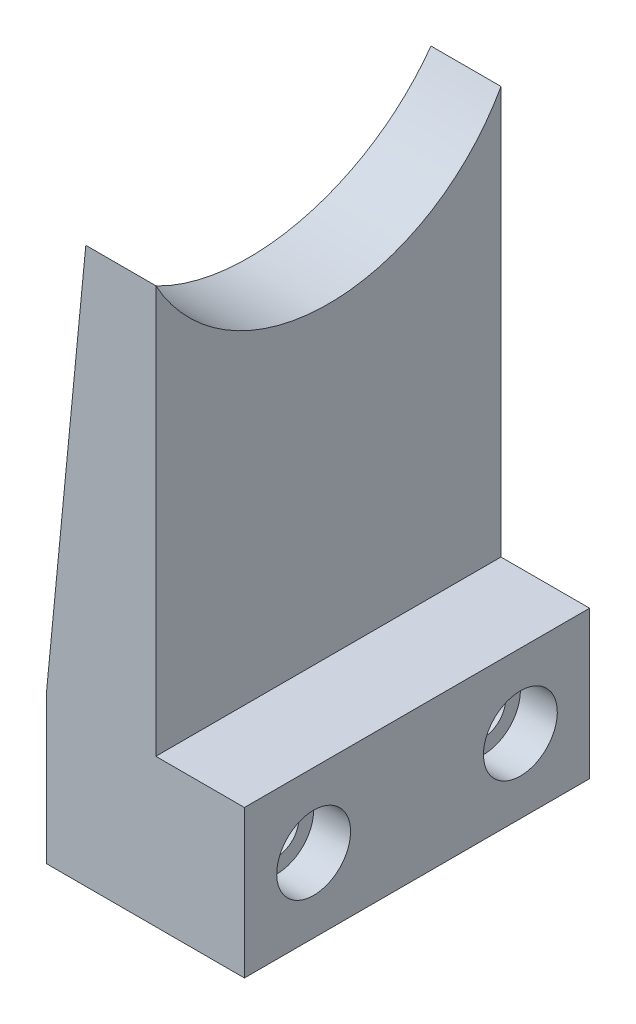
SolidWorks part; units mm, degrees
ref_plane "Front Plane" through (0, 0, 0) normal (0, 0, 1) x (1, 0, 0)
ref_plane "Top Plane" through (0, 0, 0) normal (0, 1, 0) x (1, 0, 0)
ref_plane "Right Plane" through (0, 0, 0) normal (1, 0, 0) x (0, 0, -1)
sketch "Gripper Attachment Base Sketch" plane through (0, 0, 0) normal (0, 0, 1) x (1, 0, 0)
  line L5 (5.5563, 7.5) -> (-5.5562, 7.5)
  line L6 (5.5563, 7.5) -> (5.5563, -7.5)
  line L7 (5.5563, -7.5) -> (-5.5562, -7.5)
  line L8 (-5.5562, 7.5) -> (-5.5562, -7.5)
  line L9 (5.5563, 7.5) -> (-5.5562, -7.5) construction
  line L10 (5.5563, -7.5) -> (-5.5562, 7.5) construction
  point P0 (0, 0)
  dimension "D1" = 11.1125
  dimension "D2" = 15
extrude "Gripper Attachment Base" add sketch "Gripper Attachment Base Sketch" along normal blind 35.0589 contours L7 L8 L5 L6
sketch "Through-Holes Sketch" plane through (5.5563, 0, 0) normal (1, 0, 0) x (0, 0, -1)
  line L1 (-35.0589, 7.5) -> (0, 7.5) construction
  circle A0 centre (-28.0294, 0) radius 2.25
  circle A1 centre (-7.0294, 0) radius 2.25
  point P5 (-17.5294, 7.5)
  dimension "D1" = 4.5
  dimension "D2" = 4.5
  dimension "D3" = 21
  dimension "D4" = 10.5
  dimension "D5" = 7.5
extrude "Screw Through-Holes" cut sketch "Through-Holes Sketch" against normal through all
sketch "Socket Recesses Sketch" plane through (5.5563, 0, 0) normal (1, 0, 0) x (0, 0, -1)
  circle A0 centre (-28.0294, 0) radius 3.75
  circle A1 centre (-7.0294, 0) radius 3.75
  circle A2 centre (-28.0294, 0) radius 2.25 construction
  circle A3 centre (-7.0294, 0) radius 2.25 construction
  dimension "D1" = 7.5
  dimension "D2" = 7.5
extrude "Socket Recesses" cut sketch "Socket Recesses Sketch" against normal blind 3.75
sketch "Finger Cavity Sketch" plane through (-5.5562, 0, 0) normal (-1, 0, 0) x (0, 0, 1)
  line L0 (2.5294, 7.5) -> (2.5294, -7.5)
  line L1 (0, 7.5) -> (35.0589, 7.5)
  line L2 (0, 7.5) -> (0, -7.5)
  line L3 (0, -7.5) -> (35.0589, -7.5)
  line L4 (35.0589, 7.5) -> (35.0589, -7.5)
  line L9 (32.5294, 7.5) -> (32.5294, -7.5)
  line M13 (0, 7.5) -> (0, -7.5)
  line M14 (0, -7.5) -> (35.0589, -7.5)
  line M15 (35.0589, -7.5) -> (35.0589, 7.5)
  line M16 (35.0589, 7.5) -> (0, 7.5)
  dimension "D1" = 30
  dimension "D2" = 2.5294
extrude "Finger Cavity" add sketch "Finger Cavity Sketch" along normal blind 9 contours L0 M16 M13 M14 | L9 L3 M16 M15
ref_plane "Electronics Plate Plane" through (-3.4437, 0, 0) normal (1, 0, 0) x (0, 0, -1)
sketch "Thickener Base Sketch" plane through (-3.4437, 0, 0) normal (1, 0, 0) x (0, 0, -1)
  line L0 (-35.0589, -7.5) -> (-35.0589, 7.5) construction
  line L6 (0, 7.5) -> (-35.0589, 7.5)
  line L7 (0, 7.5) -> (0, 48.8959)
  line L9 (-35.0589, 7.5) -> (-35.0589, 48.8959)
  arc A1 (-35.0589, 48.8959) -> (0, 48.8959) centre (-17.5294, 58.525) ccw
  dimension "D3" = 41.3959
  dimension "D4" = 20
extrude "Thickener Base" add sketch "Thickener Base Sketch" against normal up to surface (11.1125 mm away) up to face at (-14.5563, 0, 1.2647)
sketch "Define Thickness Plane 1" plane through (0, 0, 35.0589) normal (0, 0, 1) x (1, 0, 0)
  line L0 (-14.5563, 7.5) -> (-10.5563, 48.8959) construction
  line L1 (-14.5563, -7.5) -> (-14.5563, 48.8959) construction
  line L2 (-14.5563, 48.8959) -> (-3.4438, 48.8959) construction
  dimension "D1" = 4
sketch "Derfine Thickness Plane 2" plane through (0, 0, 0) normal (0, 0, -1) x (-1, 0, 0)
  line L0 (14.5563, 7.5) -> (10.5563, 48.8959) construction
  line L1 (14.5563, 48.8959) -> (14.5563, -7.5) construction
  line L2 (14.5563, 48.8959) -> (3.4438, 48.8959) construction
  dimension "D1" = 4
ref_plane "Thickness Plane" through (-15.1396, 1.4629, 0) normal (0.9954, -0.0962, 0) x (0, 0, -1)
sketch "Thickness Cutoff Sketch" plane through (-15.1396, 1.4629, 0) normal (0.9954, -0.0962, 0) x (0, 0, -1)
  line L1 (-48.3458, -8.0425) -> (13.6509, -8.0425)
  line L2 (-48.3458, -8.0425) -> (-48.3458, 56.793)
  line L3 (-48.3458, 56.793) -> (13.6509, 56.793)
  line L4 (13.6509, -8.0425) -> (13.6509, 56.793)
extrude "Thickness Cutoff" cut sketch "Thickness Cutoff Sketch" against normal through all
